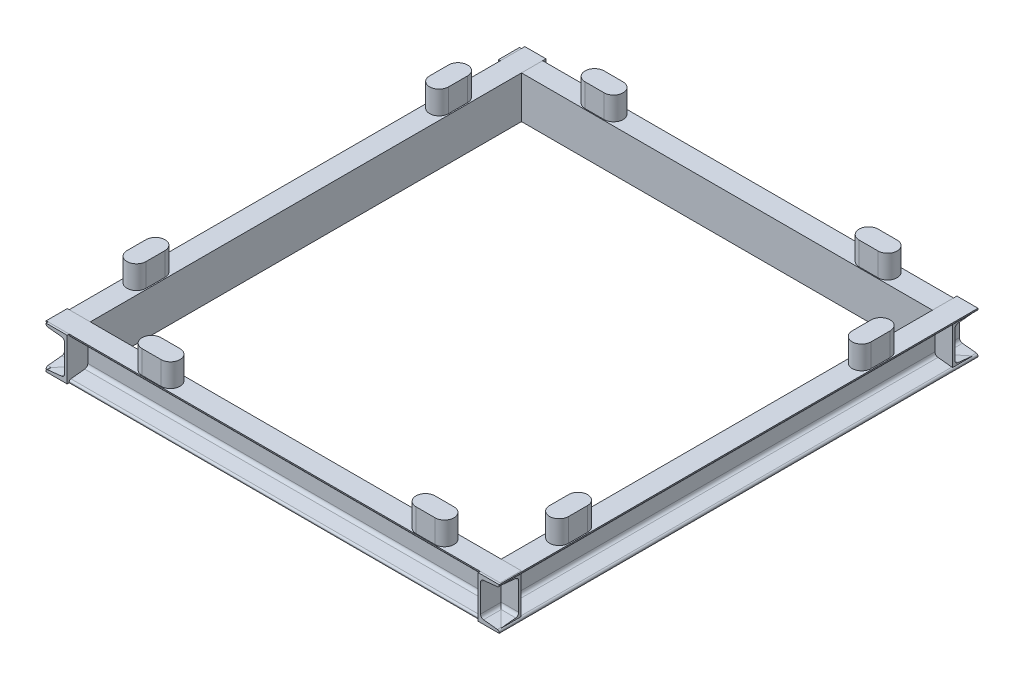
SolidWorks part; units mm, degrees
ref_plane "Front Plane" through (0, 0, 0) normal (0, 0, 1) x (1, 0, 0)
ref_plane "Top Plane" through (0, 0, 0) normal (0, 1, 0) x (1, 0, 0)
ref_plane "Right Plane" through (0, 0, 0) normal (1, 0, 0) x (0, 0, -1)
sketch "Sketch1" plane through (0, 0, 0) normal (0, 1, 0) x (1, 0, 0)
  line L1 (0, 0) -> (1076, 0)
  line L2 (0, 0) -> (0, 1135)
  line L3 (0, 1135) -> (1076, 1135)
  line L4 (1076, 0) -> (1076, 1135)
  dimension "D1" = 1135
  dimension "D2" = 1076
other "C channel 100 X 10(1)"
ref_plane "Plane1" through (1076, 0, 0) normal (0, 0, -1) x (-1, 0, 0)
sketch "Sketch12" plane through (0, 0, 0) normal (0, 0, -1) x (-1, 0, 0)
  line L0 (50, 100) -> (0, 100)
  line L1 (50, 0) -> (0, 0)
  line L2 (0, 100) -> (0, 0)
  line L6 (50, 100) -> (50, 98.3701)
  line L7 (50, 0) -> (50, 1.6299)
  line L12 (5.9, 82.48) -> (5.9, 17.52)
  line L17 (13.0638, 90.4362) -> (45.9704, 93.8948)
  line L18 (13.0638, 9.5638) -> (45.9704, 6.1052)
  arc A0 (45.9704, 93.8948) -> (50, 98.3701) centre (45.5, 98.3701) ccw
  arc A1 (45.9704, 6.1052) -> (50, 1.6299) centre (45.5, 1.6299) cw
  arc A9 (5.9, 17.52) -> (13.0638, 9.5638) centre (13.9, 17.52) ccw
  arc A10 (5.9, 82.48) -> (13.0638, 90.4362) centre (13.9, 82.48) cw
  point P8 (0, 50)
  point P9 (5.9, 50)
  point P10 (25, 100)
  point P11 (25, 0)
  point P12 (50, 5.6817)
  point P13 (50, 94.3183)
  point P14 (0, 0)
  dimension "D4" = 4.5
  dimension "RI" = 8
  dimension "D2" = 6
  dimension "D3" = 17.52
  dimension "Depth" = 100
  dimension "BF" = 50
  dimension "TW" = 5.9
  dimension "d1" = 64.96
move or copy body "Body-Move/Copy1" bodies to move or copy 103 copy no translate (-47.4435, 0, 0)
move or copy body "Body-Move/Copy2" bodies to move or copy 101 copy no translate (54.5532, 0, 0)
move or copy body "Body-Move/Copy3" bodies to move or copy 104 copy no translate (0, 0, -54.9281)
move or copy body "Body-Move/Copy4" bodies to move or copy 102 copy no translate (0, 0, 57.9702)
sketch "Sketch13" plane through (0, 100, 0) normal (0, 1, 0) x (1, 0, 0)
  line L0 (29.2564, 951.9559) -> (29.2564, 906.9559) construction
  line L1 (51.7564, 951.9559) -> (51.7564, 906.9559)
  line L2 (6.7564, 951.9559) -> (6.7564, 906.9559)
  line L3 (29.2564, 234.7623) -> (29.2564, 189.7623) construction
  line L4 (51.7564, 234.7623) -> (51.7564, 189.7623)
  line L5 (6.7564, 234.7623) -> (6.7564, 189.7623)
  line L6 (1053.3622, 929.4559) -> (1053.3622, 884.4559) construction
  line L7 (1075.8622, 929.4559) -> (1075.8622, 884.4559)
  line L8 (1030.8622, 929.4559) -> (1030.8622, 884.4559)
  line L9 (1053.3622, 212.2623) -> (1053.3622, 167.2623) construction
  line L10 (1075.8622, 212.2623) -> (1075.8622, 167.2623)
  line L11 (1030.8622, 212.2623) -> (1030.8622, 167.2623)
  line L12 (203.2711, 1101.5643) -> (248.2711, 1101.5643) construction
  line L13 (203.2711, 1124.0643) -> (248.2711, 1124.0643)
  line L14 (203.2711, 1079.0643) -> (248.2711, 1079.0643)
  line L15 (852.7067, 1101.5643) -> (897.7067, 1101.5643) construction
  line L16 (852.7067, 1124.0643) -> (897.7067, 1124.0643)
  line L17 (852.7067, 1079.0643) -> (897.7067, 1079.0643)
  line L18 (225.7711, 28.9087) -> (270.7711, 28.9087) construction
  line L19 (225.7711, 51.4087) -> (270.7711, 51.4087)
  line L20 (225.7711, 6.4087) -> (270.7711, 6.4087)
  line L21 (875.2067, 28.9087) -> (920.2067, 28.9087) construction
  line L22 (875.2067, 51.4087) -> (920.2067, 51.4087)
  line L23 (875.2067, 6.4087) -> (920.2067, 6.4087)
  arc A0 (51.7564, 951.9559) -> (6.7564, 951.9559) centre (29.2564, 951.9559) ccw
  arc A1 (6.7564, 906.9559) -> (51.7564, 906.9559) centre (29.2564, 906.9559) ccw
  arc A2 (51.7564, 234.7623) -> (6.7564, 234.7623) centre (29.2564, 234.7623) ccw
  arc A3 (6.7564, 189.7623) -> (51.7564, 189.7623) centre (29.2564, 189.7623) ccw
  arc A4 (1075.8622, 929.4559) -> (1030.8622, 929.4559) centre (1053.3622, 929.4559) ccw
  arc A5 (1030.8622, 884.4559) -> (1075.8622, 884.4559) centre (1053.3622, 884.4559) ccw
  arc A6 (1075.8622, 212.2623) -> (1030.8622, 212.2623) centre (1053.3622, 212.2623) ccw
  arc A7 (1030.8622, 167.2623) -> (1075.8622, 167.2623) centre (1053.3622, 167.2623) ccw
  arc A8 (203.2711, 1124.0643) -> (203.2711, 1079.0643) centre (203.2711, 1101.5643) ccw
  arc A9 (248.2711, 1079.0643) -> (248.2711, 1124.0643) centre (248.2711, 1101.5643) ccw
  arc A10 (852.7067, 1124.0643) -> (852.7067, 1079.0643) centre (852.7067, 1101.5643) ccw
  arc A11 (897.7067, 1079.0643) -> (897.7067, 1124.0643) centre (897.7067, 1101.5643) ccw
  arc A12 (225.7711, 51.4087) -> (225.7711, 6.4087) centre (225.7711, 28.9087) ccw
  arc A13 (270.7711, 6.4087) -> (270.7711, 51.4087) centre (270.7711, 28.9087) ccw
  arc A14 (875.2067, 51.4087) -> (875.2067, 6.4087) centre (875.2067, 28.9087) ccw
  arc A15 (920.2067, 6.4087) -> (920.2067, 51.4087) centre (920.2067, 28.9087) ccw
  point P2 (29.2564, 929.4559)
  point P7 (29.2564, 884.4559)
  point P8 (29.2564, 974.4559)
  point P11 (29.2564, 212.2623)
  point P16 (29.2564, 167.2623)
  point P17 (29.2564, 257.2623)
  point P20 (1053.3622, 906.9559)
  point P25 (1053.3622, 861.9559)
  point P26 (1053.3622, 951.9559)
  point P29 (1053.3622, 189.7623)
  point P36 (225.7711, 1101.5643)
  point P41 (225.7711, 1056.5643)
  point P42 (225.7711, 1146.5643)
  point P45 (875.2067, 1101.5643)
  point P52 (248.2711, 28.9087)
  point P59 (897.7067, 28.9087)
  dimension "D1" = 90
  dimension "D2" = 45
extrude "Boss-Extrude1" add sketch "Sketch13" along normal blind 55 separate body
